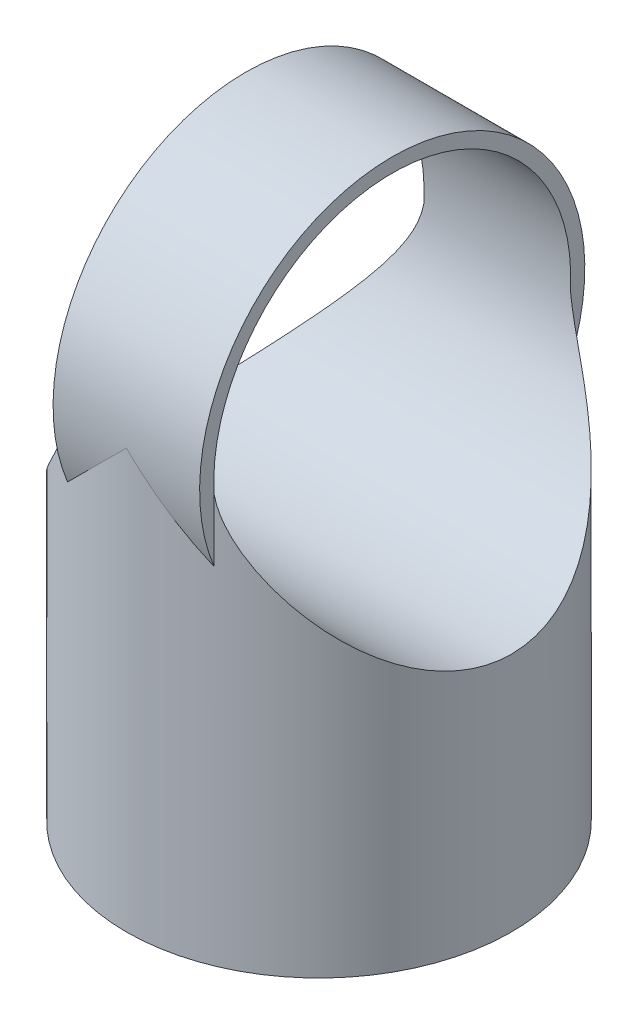
SolidWorks part; units mm, degrees
ref_plane "Front Plane" through (0, 0, 0) normal (0, 0, 1) x (1, 0, 0)
ref_plane "Top Plane" through (0, 0, 0) normal (0, 1, 0) x (1, 0, 0)
ref_plane "Right Plane" through (0, 0, 0) normal (1, 0, 0) x (0, 0, -1)
sketch "Sketch1" plane through (0, 0, 0) normal (1, 0, 0) x (0, 0, -1)
  circle A0 centre (0, 0) radius 107.95
  circle A1 centre (0, 0) radius 116.84
extrude "Boss-Extrude1" add sketch "Sketch1" along normal mid plane 88.9
sketch "Sketch13" plane through (0, 0, 0) normal (1, 0, 0) x (0, 0, -1)
  line L0 (-116.84, 0) -> (-116.84, -254.257)
  line L1 (-116.84, -254.257) -> (0, -254.257)
  line L3 (0, -116.84) -> (0, -254.257)
  circle A3 centre (0, 0) radius 116.84
  arc A4 (-116.84, 0) -> (0, -116.84) centre (0, 0) ccw
  dimension "D1" = 0
revolve "Revolve3" add sketch "Sketch13" angle 360 about L3
sketch "Sketch14" plane through (0, 0, 0) normal (1, 0, 0) x (0, 0, -1)
  circle A0 centre (0, 0) radius 108.2475
extrude "Cut-Extrude6" cut sketch "Sketch14" along normal blind 288.798 and the other way blind 154.94
sketch "Sketch15" plane through (0, -254.257, 0) normal (0, -1, 0) x (1, 0, 0)
  circle A0 centre (0, 0) radius 76.2
extrude "Cut-Extrude7" cut sketch "Sketch15" against normal blind 63.5
